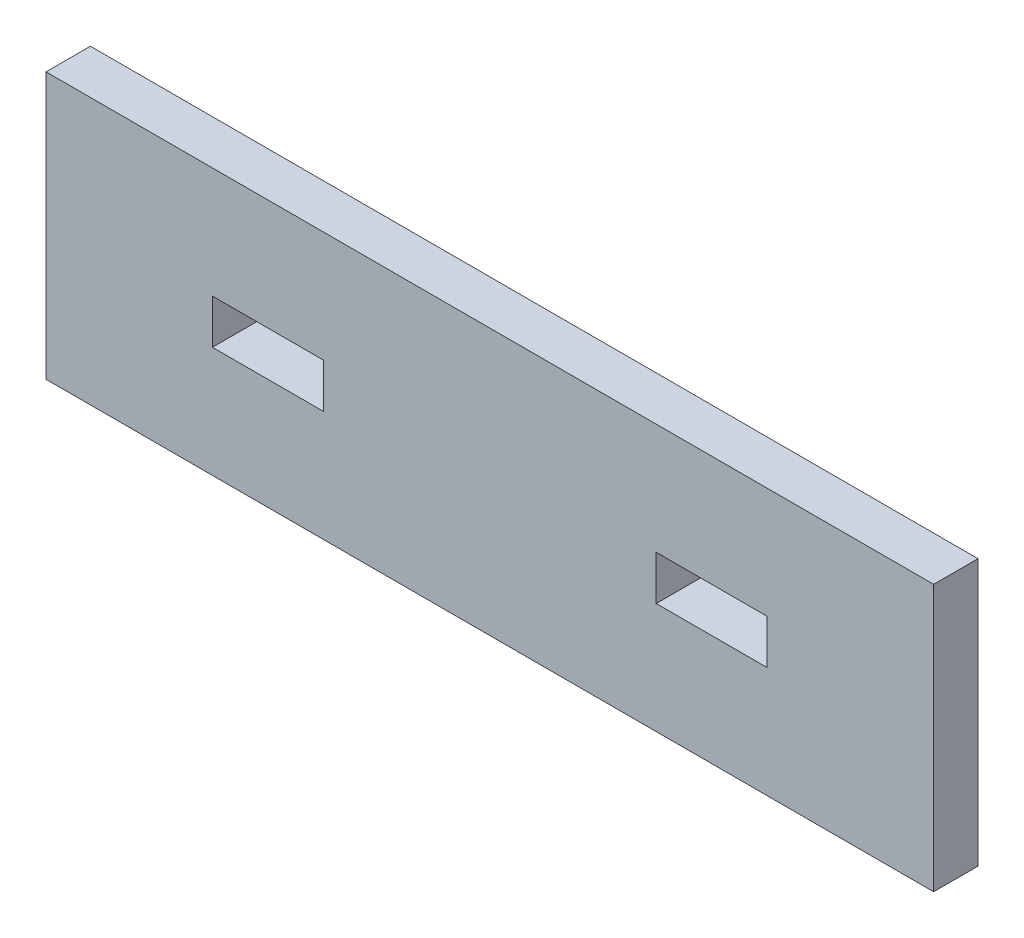
SolidWorks part; units mm, degrees
ref_plane "Front Plane" through (0, 0, 0) normal (0, 0, 1) x (1, 0, 0)
ref_plane "Top Plane" through (0, 0, 0) normal (0, 1, 0) x (1, 0, 0)
ref_plane "Right Plane" through (0, 0, 0) normal (1, 0, 0) x (0, 0, -1)
sketch "Sketch1" plane through (0, 0, 0) normal (0, 0, 1) x (1, 0, 0)
  line L0 (0, 12) -> (106.3382, 12) construction
  line L1 (0, 0) -> (80, 0)
  line L2 (0, 0) -> (0, 24)
  line L3 (0, 24) -> (80, 24)
  line L4 (80, 0) -> (80, 24)
  line L5 (40, 24) -> (40, -9.4135) construction
  line L6 (65, 10) -> (55, 14) construction
  line L7 (15, 14) -> (25, 14)
  line L8 (15, 14) -> (15, 10)
  line L9 (15, 10) -> (25, 10)
  line L10 (25, 14) -> (25, 10)
  line L11 (15, 14) -> (25, 10) construction
  line L12 (15, 10) -> (25, 14) construction
  line L13 (65, 14) -> (55, 10) construction
  line L14 (55, 14) -> (55, 10)
  line L15 (65, 10) -> (55, 10)
  line L16 (65, 14) -> (65, 10)
  line L17 (65, 14) -> (55, 14)
  point P9 (20, 12)
  point P18 (60, 12)
  dimension "D1" = 80
  dimension "D2" = 24
  dimension "D3" = 4
  dimension "D4" = 10
  dimension "D5" = 15
extrude "Boss-Extrude1" add sketch "Sketch1" along normal blind 4
